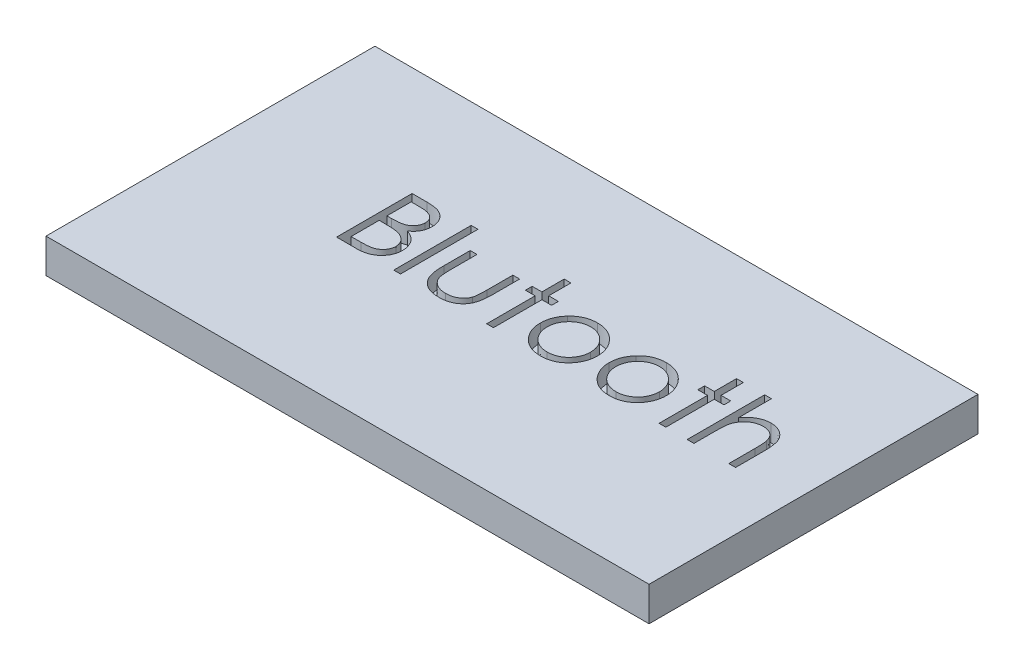
SolidWorks part; units mm, degrees
material "Silicon"
ref_plane "Front Plane" through (0, 0, 0) normal (0, 0, 1) x (1, 0, 0)
ref_plane "Top Plane" through (0, 0, 0) normal (0, 1, 0) x (1, 0, 0)
ref_plane "Right Plane" through (0, 0, 0) normal (1, 0, 0) x (0, 0, -1)
sketch "Sketch1" plane through (0, 0, 0) normal (0, 1, 0) x (1, 0, 0)
  line L1 (-13.97, -7.62) -> (13.97, -7.62)
  line L2 (-13.97, -7.62) -> (-13.97, 7.62)
  line L3 (-13.97, 7.62) -> (13.97, 7.62)
  line L4 (13.97, -7.62) -> (13.97, 7.62)
  line L5 (-13.97, -7.62) -> (13.97, 7.62) construction
  line L6 (-13.97, 7.62) -> (13.97, -7.62) construction
  point P0 (0, 0)
  dimension "D1" = 15.24
  dimension "D2" = 27.94
extrude "Boss-Extrude1" add sketch "Sketch1" along normal blind 1.5875
sketch "Sketch2" plane through (0, 1.5875, 0) normal (0, 1, 0) x (1, 0, 0)
  text T0 "Blutooth"
  point P1 (-12.061, 1.3341)
extrude "Cut-Extrude1" cut sketch "Sketch2" against normal blind 0.7937
